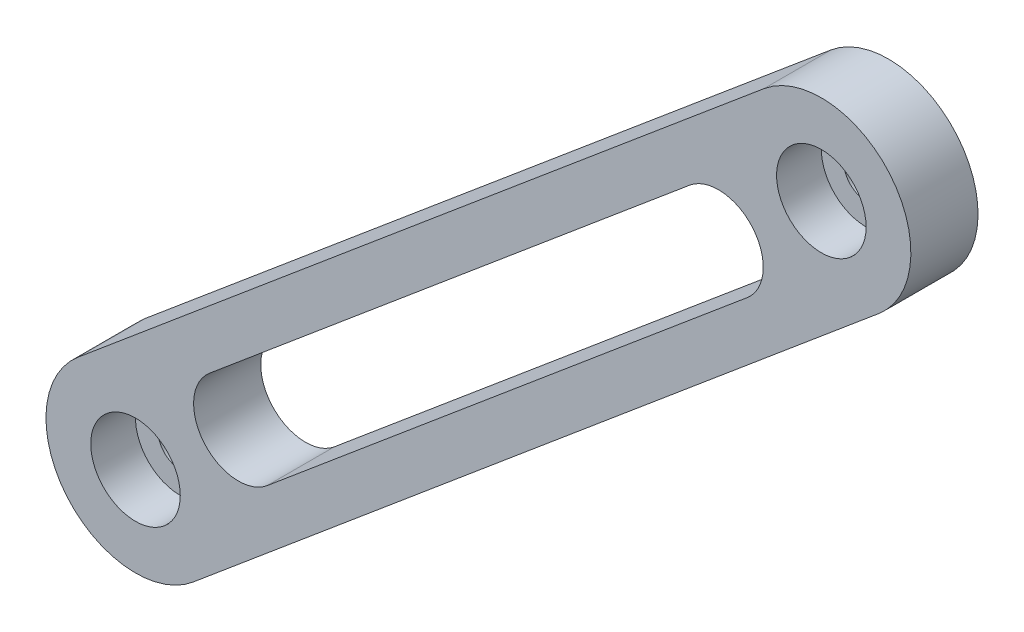
SolidWorks part; units mm, degrees
ref_plane "Front Plane" through (0, 0, 0) normal (0, 0, 1) x (1, 0, 0)
ref_plane "Top Plane" through (0, 0, 0) normal (0, 1, 0) x (1, 0, 0)
ref_plane "Right Plane" through (0, 0, 0) normal (1, 0, 0) x (0, 0, -1)
sketch "Sketch1" plane through (0, 0, 0) normal (0, 0, 1) x (1, 0, 0)
  line L0 (0, 0) -> (179.8502, 0) construction
  line L1 (8.1025, 0) -> (496.1402, 409.5122) construction
  line L2 (496.1402, 409.5122) -> (568.3483, 0) construction
  line L5 (460.3559, 412.643) -> (265.7806, 249.3749)
  line L7 (493.0095, 373.7279) -> (298.4342, 210.4598)
  line L9 (447.4964, 368.6952) -> (311.2937, 254.4076) construction
  line L10 (455.6598, 358.9665) -> (319.4571, 244.6788)
  line L11 (439.333, 378.424) -> (303.1303, 264.1363)
  line L12 (282.1074, 229.9174) -> (265.7806, 249.3749) construction
  line L13 (282.1074, 229.9174) -> (298.4342, 210.4598) construction
  line L14 (460.3559, 412.643) -> (493.0095, 373.7279) construction
  arc A0 (455.6598, 358.9665) -> (439.333, 378.424) centre (447.4964, 368.6952) ccw
  arc A1 (303.1303, 264.1363) -> (319.4571, 244.6788) centre (311.2937, 254.4076) ccw
  circle A2 centre (282.1074, 229.9174) radius 6.35
  arc A3 (265.7806, 249.3749) -> (298.4342, 210.4598) centre (282.1074, 229.9174) ccw
  circle A4 centre (476.6827, 393.1854) radius 6.35
  arc A5 (460.3559, 412.643) -> (493.0095, 373.7279) centre (476.6827, 393.1854) cw
  point P12 (379.395, 311.5514)
  point P24 (476.6827, 393.1854)
  dimension "D6" = 12.7
  dimension "D7" = 12.7
  dimension "D4" = 25.4
  dimension "D3" = 25.4
  dimension "D1" = 40
  dimension "D2" = 80
  dimension "D5" = 177.8
  dimension "D8" = 38.1
  dimension "D9" = 38.1
extrude "Boss-Extrude1" add sketch "Sketch1" along normal blind 19.05
sketch "Sketch2" plane through (0, 0, 19.05) normal (0, 0, 1) x (1, 0, 0)
  circle A0 centre (282.1074, 229.9174) radius 12.7
  circle A1 centre (476.6827, 393.1854) radius 12.7
  dimension "D1" = 25.4
extrude "Cut-Extrude1" cut sketch "Sketch2" against normal blind 12.7
